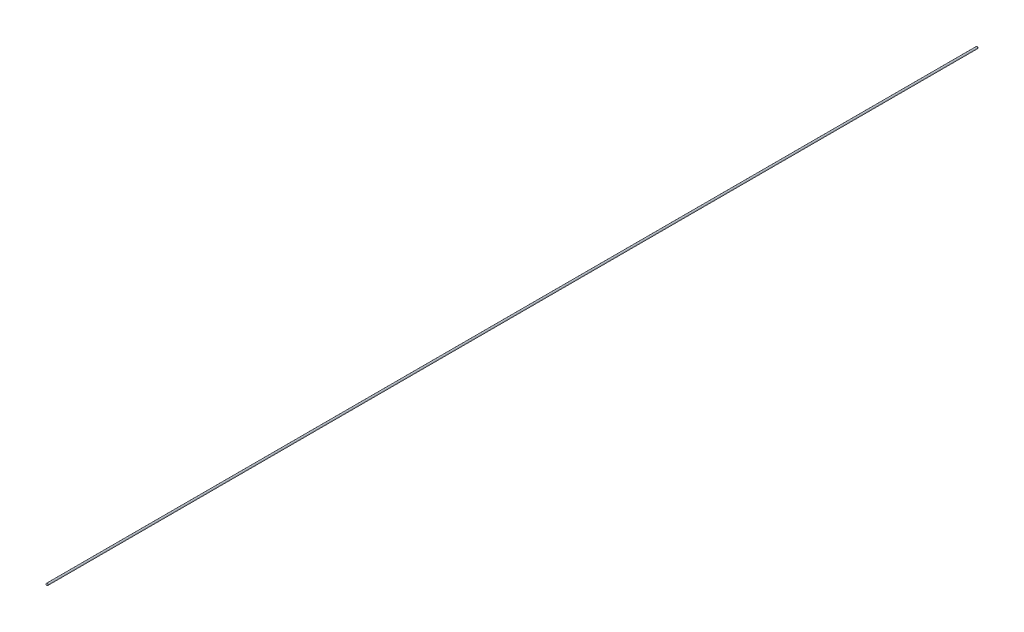
SolidWorks part; units mm, degrees
ref_plane "Front Plane" through (0, 0, 0) normal (0, 0, 1) x (1, 0, 0)
ref_plane "Top Plane" through (0, 0, 0) normal (0, 1, 0) x (1, 0, 0)
ref_plane "Right Plane" through (0, 0, 0) normal (1, 0, 0) x (0, 0, -1)
sketch "Sketch3" plane through (0, 0, 0) normal (0, 0, 1) x (1, 0, 0)
  circle A0 centre (0, 0) radius 0.5
  dimension "D1" = 1
extrude "Boss-Extrude1" add sketch "Sketch3" along normal mid plane 500
fillet "Fillet1" radius 0.4 2 edges at (0.5, 0, 250) (0.5, 0, -250)
